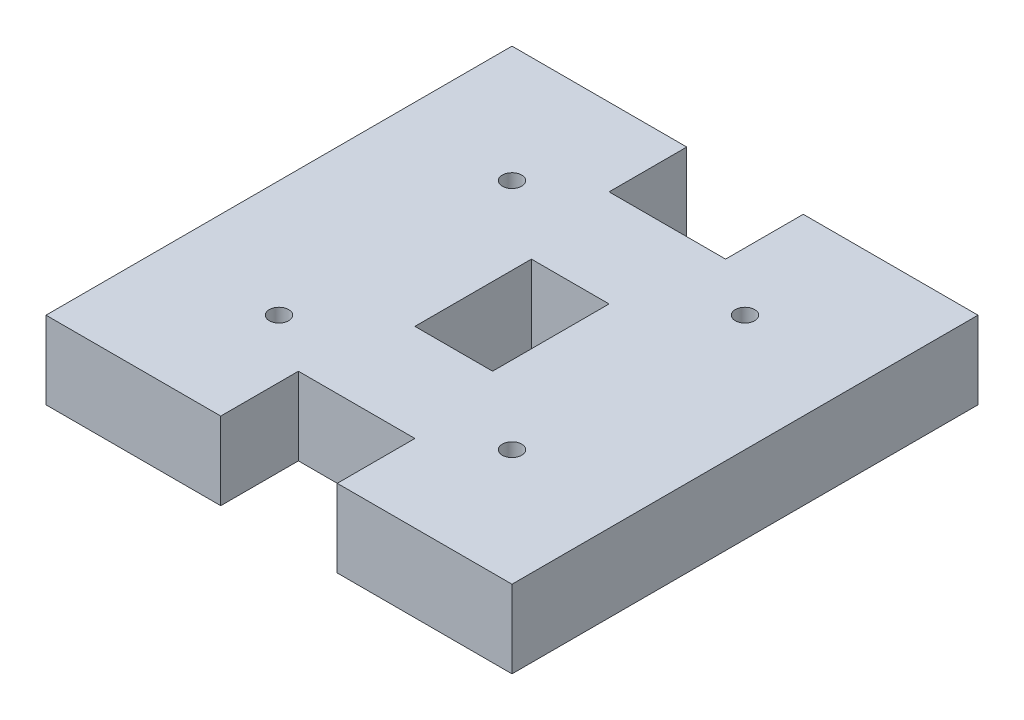
SolidWorks part; units mm, degrees
ref_plane "Plano frontal" through (0, 0, 0) normal (0, 0, 1) x (1, 0, 0)
ref_plane "Plano superior" through (0, 0, 0) normal (0, 1, 0) x (1, 0, 0)
ref_plane "Plano direito" through (0, 0, 0) normal (1, 0, 0) x (0, 0, -1)
sketch "Esboço1" plane through (0, 0, 0) normal (0, 1, 0) x (1, 0, 0)
  line L0 (0, 0) -> (60, 0)
  line L1 (60, 0) -> (60, 60)
  line L2 (60, 60) -> (0, 60)
  line L3 (0, 60) -> (0, 0)
  dimension "D1" = 60
  dimension "D2" = 60
extrude "Ressalto-extrusão1" add sketch "Esboço1" along normal blind 10
sketch "Esboço2" plane through (0, 0, 0) normal (0, 0, 1) x (1, 0, 0)
  line L0 (22.5, 10) -> (22.5, 0)
  line L1 (0, 10) -> (60, 10) construction
  line L2 (0, 0) -> (60, 0) construction
  line L3 (22.5, 0) -> (37.5, 0)
  line L4 (37.5, 0) -> (37.5, 10)
  line L5 (37.5, 10) -> (22.5, 10)
  line L6 (60, 10) -> (60, 0) construction
  dimension "D1" = 15
  dimension "D2" = 22.5
extrude "Corte-extrusão1" cut sketch "Esboço2" against normal blind 10
sketch "Esboço3" plane through (0, 0, -60) normal (0, 0, -1) x (-1, 0, 0)
  line L0 (-37.5, 10) -> (-37.5, 0)
  line L1 (-60, 10) -> (0, 10) construction
  line L2 (-60, 0) -> (0, 0) construction
  line L3 (-37.5, 0) -> (-22.5, 0)
  line L4 (-22.5, 0) -> (-22.5, 10)
  line L5 (-22.5, 10) -> (-37.5, 10)
  line L6 (0, 10) -> (0, 0) construction
  dimension "D1" = 15
  dimension "D2" = 22.5
extrude "Corte-extrusão2" cut sketch "Esboço3" against normal blind 10
sketch "Esboço4" plane through (0, 10, 0) normal (0, 1, 0) x (1, 0, 0)
  line L0 (25, 37.5) -> (35, 37.5)
  line L1 (35, 37.5) -> (35, 22.5)
  line L2 (35, 22.5) -> (25, 22.5)
  line L3 (25, 22.5) -> (25, 37.5)
  line L4 (22.5, 50) -> (37.5, 50) construction
  line L5 (0, 60) -> (0, 0) construction
  dimension "D1" = 10
  dimension "D2" = 15
  dimension "D3" = 12.5
  dimension "D4" = 25
extrude "Corte-extrusão3" cut sketch "Esboço4" against normal through all
sketch "Esboço5" plane through (0, 10, 0) normal (0, 1, 0) x (1, 0, 0)
  line L0 (60, 0) -> (60, 60) construction
  line L1 (60, 60) -> (37.5, 60) construction
  line L2 (0, 60) -> (0, 0) construction
  line L3 (37.5, 0) -> (60, 0) construction
  circle A0 centre (45, 45) radius 1.25
  circle A1 centre (15, 45) radius 1.25
  circle A2 centre (45, 15) radius 1.25
  circle A3 centre (15, 15) radius 1.25
  dimension "D1" = 2.5
  dimension "D5" = 15
  dimension "D6" = 2.5
  dimension "D8" = 15
  dimension "D10" = 15
  dimension "D2" = 15
  dimension "D3" = 15
  dimension "D7" = 15
  dimension "D4" = 2
  dimension "D9" = 2
extrude "Corte-extrusão4" cut sketch "Esboço5" against normal through all
